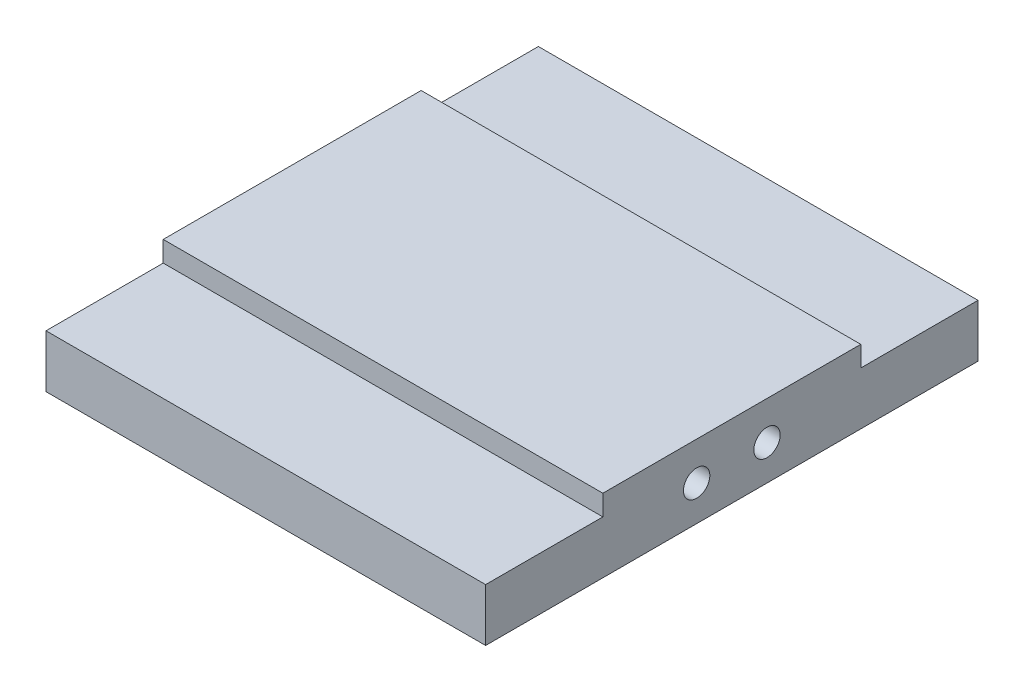
SolidWorks part; units mm, degrees
ref_plane "Front Plane" through (0, 0, 0) normal (0, 0, 1) x (1, 0, 0)
ref_plane "Top Plane" through (0, 0, 0) normal (0, 1, 0) x (1, 0, 0)
ref_plane "Right Plane" through (0, 0, 0) normal (1, 0, 0) x (0, 0, -1)
sketch "Sketch1" plane through (0, 0, 0) normal (0, 1, 0) x (1, 0, 0)
  line L1 (-37.5, 42) -> (37.5, 42)
  line L2 (-37.5, 42) -> (-37.5, -42)
  line L3 (-37.5, -42) -> (37.5, -42)
  line L4 (37.5, 42) -> (37.5, -42)
  line L5 (-37.5, 42) -> (37.5, -42) construction
  line L6 (-37.5, -42) -> (37.5, 42) construction
  point P0 (0, 0)
  dimension "D1" = 84
  dimension "D2" = 75
extrude "Boss-Extrude1" add sketch "Sketch1" along normal blind 12.5
sketch "Sketch2" plane through (0, 0, 0) normal (0, -1, 0) x (1, 0, 0)
  line L5 (37.5, 42) -> (37.5, -42) construction
  line L8 (37.5, 0) -> (27.5, 0) construction
  line L10 (27.5, 11) -> (21.25, 11)
  line L11 (27.5, 11) -> (27.5, -11)
  line L12 (27.5, -11) -> (21.25, -11)
  line L13 (21.25, 11) -> (21.25, -11)
  point P0 (27.5, 16.3269)
  point P19 (0, 0)
  point P20 (27.5, 0)
  dimension "D1" = 22
  dimension "D3" = 10
  dimension "D4" = 6.25
extrude "Cut-Extrude1" cut sketch "Sketch2" against normal blind 12
sketch "Sketch3" plane through (37.5, 0, 0) normal (1, 0, 0) x (0, 0, -1)
  line L0 (0, 0) -> (0, 12) construction
  line L3 (11, 12) -> (11, 0) construction
  line L4 (0, 6) -> (-6, 6) construction
  line L5 (0, 6) -> (6, 6) construction
  circle A0 centre (-6, 6) radius 2.25
  circle A1 centre (6, 6) radius 2.25
  dimension "D1" = 4.5
  dimension "D2" = 6
extrude "Cut-Extrude2" cut sketch "Sketch3" against normal through all
sketch "Sketch4" plane through (0, 12.5, 0) normal (0, 1, 0) x (1, 0, 0)
  line L0 (37.5, -42) -> (37.5, 42) construction
  line L1 (-37.5, 42) -> (37.5, 42)
  line L2 (-37.5, 42) -> (-37.5, 22)
  line L3 (-37.5, 22) -> (37.5, 22)
  line L4 (37.5, 42) -> (37.5, 22)
  line L6 (-37.5, -42) -> (37.5, -42)
  line L7 (-37.5, -42) -> (-37.5, -22)
  line L8 (-37.5, -22) -> (37.5, -22)
  line L9 (37.5, -42) -> (37.5, -22)
  dimension "D1" = 20
extrude "Cut-Extrude3" cut sketch "Sketch4" against normal blind 3.5
